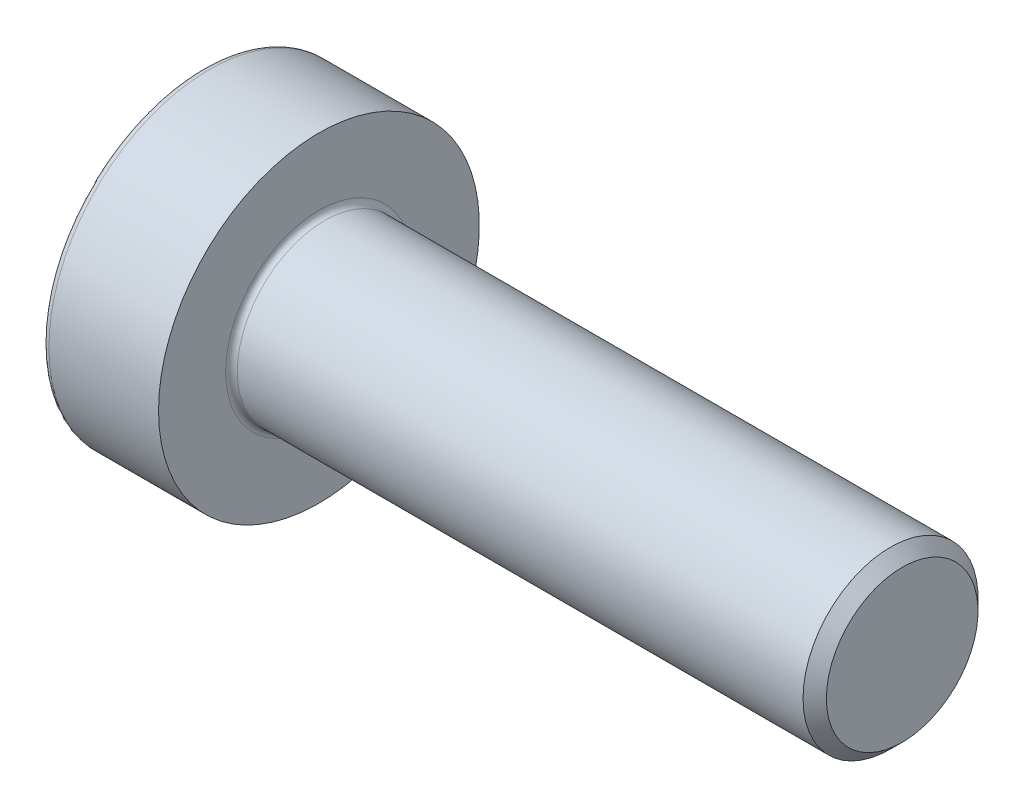
SolidWorks part; units mm, degrees
ref_plane "Front Plane" through (0, 0, 0) normal (0, 0, 1) x (1, 0, 0)
ref_plane "Top Plane" through (0, 0, 0) normal (0, 1, 0) x (1, 0, 0)
ref_plane "Right Plane" through (0, 0, 0) normal (1, 0, 0) x (0, 0, -1)
sketch "Sketch1" plane through (0, 0, 0) normal (0, 0, 1) x (1, 0, 0)
  line L0 (0, 0) -> (0, 2.75)
  line L1 (0, 2.75) -> (2, 2.75)
  line L2 (2, 2.75) -> (2, 0)
  line L3 (0, 0) -> (4.2799, 0) construction
  line L4 (2, 0) -> (12, 0)
  line L5 (12, 0) -> (12, 1.5)
  line L6 (12, 1.5) -> (2, 1.5)
  dimension "D1" = 10
  dimension "D2" = 2
  dimension "D3" = 2.75
  dimension "D4" = 1.5
revolve "Revolve1" add sketch "Sketch1" angle 360 about L3
fillet "Fillet1" radius 0.1 1 edges at (2, 0, 1.5)
fillet "Fillet2" radius 0.12 1 edges at (0, 0, 2.75)
chamfer "Chamfer1" distance 0.2 angle 45 1 edges at (12, 0, 1.5)
sketch "Sketch2" plane through (0, 0, 0) normal (-1, 0, 0) x (0, 0, 1)
  line L1 (0, 1.4434) -> (-1.25, 0.7217)
  line L2 (-1.25, 0.7217) -> (-1.25, -0.7217)
  line L3 (-1.25, -0.7217) -> (0, -1.4434)
  line L4 (0, -1.4434) -> (1.25, -0.7217)
  line L5 (1.25, -0.7217) -> (1.25, 0.7217)
  line L6 (1.25, 0.7217) -> (0, 1.4434)
  circle A0 centre (0, 0) radius 1.25 construction
extrude "Extrude1" cut sketch "Sketch2" against normal blind 1
